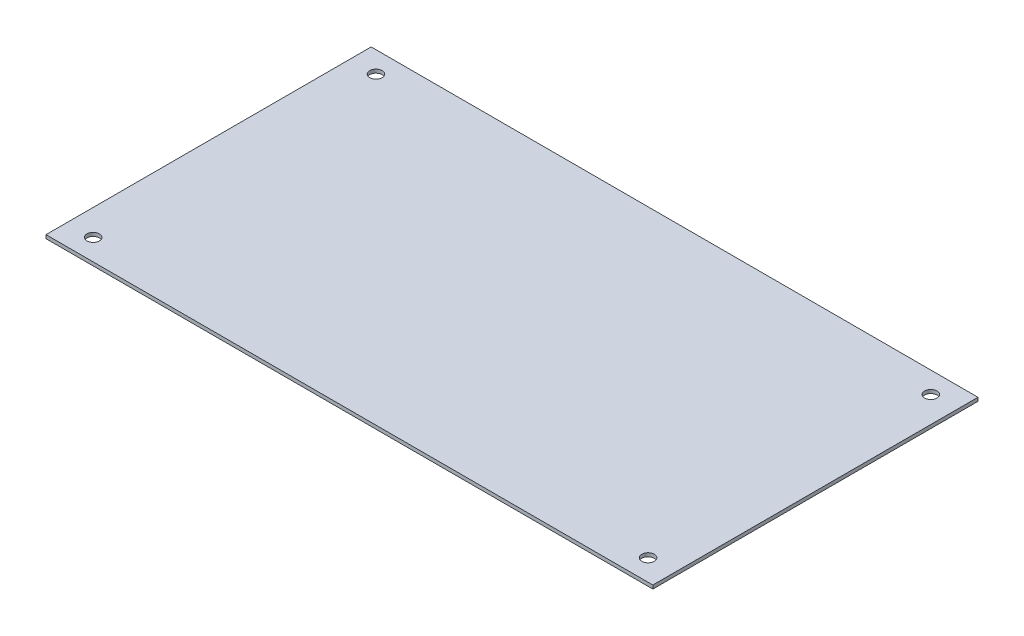
SolidWorks part; units mm, degrees
ref_plane "Front Plane" through (0, 0, 0) normal (0, 0, 1) x (1, 0, 0)
ref_plane "Top Plane" through (0, 0, 0) normal (0, 1, 0) x (1, 0, 0)
ref_plane "Right Plane" through (0, 0, 0) normal (1, 0, 0) x (0, 0, -1)
sketch "Sketch1" plane through (0, 0, 0) normal (0, 1, 0) x (1, 0, 0)
  line L1 (-85.85, -46) -> (85.85, -46)
  line L2 (-85.85, -46) -> (-85.85, 46)
  line L3 (-85.85, 46) -> (85.85, 46)
  line L4 (85.85, -46) -> (85.85, 46)
  line L5 (-85.85, -46) -> (85.85, 46) construction
  line L6 (-85.85, 46) -> (85.85, -46) construction
  circle A0 centre (-78.5, 40) radius 1.75
  circle A1 centre (78.5, 40) radius 1.75
  circle A2 centre (-78.5, -40) radius 1.75
  circle A3 centre (78.5, -40) radius 1.75
  point P0 (0, 0)
  dimension "D4" = 3.5
  dimension "D1" = 171.7
  dimension "D2" = 92
  dimension "D3" = 6
  dimension "D5" = 7.35
  dimension "D8" = 157
  dimension "D9" = 80
  dimension "D6" = 2
  dimension "D7" = 2
extrude "Boss-Extrude1" add sketch "Sketch1" along normal blind 1
